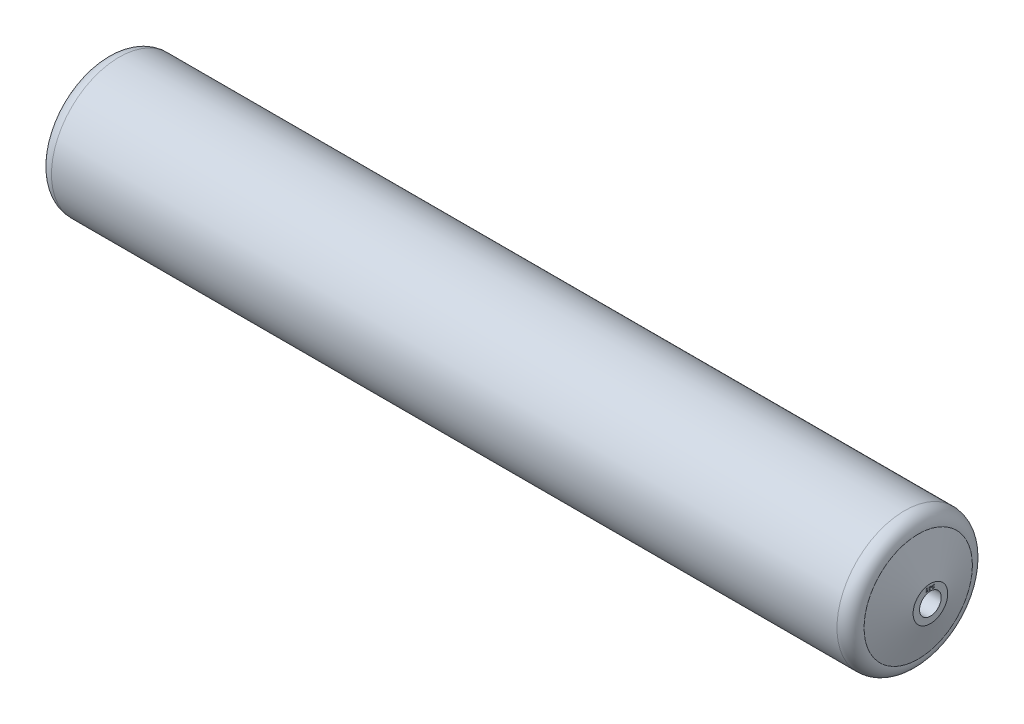
SolidWorks part; units mm, degrees
ref_plane "Plan de face" through (0, 0, 0) normal (0, 0, 1) x (1, 0, 0)
ref_plane "Plan de dessus" through (0, 0, 0) normal (0, 1, 0) x (1, 0, 0)
ref_plane "Plan de droite" through (0, 0, 0) normal (1, 0, 0) x (0, 0, -1)
sketch "Esquisse1" plane through (0, 0, 0) normal (0, 0, 1) x (1, 0, 0)
  line L0 (-154.5, 6.4) -> (-154.5, 0)
  line L1 (-154.5, 0) -> (154.5, 0)
  line L2 (154.5, 0) -> (154.5, 6.4)
  line L3 (154.5, 6.4) -> (150, 20)
  line L4 (145, 25) -> (-145, 25)
  line L5 (-150, 20) -> (-154.5, 6.4)
  line L6 (-154.5, 0) -> (154.5, 0) construction
  arc A0 (150, 20) -> (145, 25) centre (145, 20) ccw
  arc A1 (-145, 25) -> (-150, 20) centre (-145, 20) ccw
revolve "Révolution1" add sketch "Esquisse1" angle 360 about L6
sketch "Esquisse2" plane through (154.5, 0, 0) normal (1, 0, 0) x (0, 0, -1)
  line L0 (-0.221, 4.8437) -> (0.0166, 4.8437)
  line L1 (0.0166, 5.625) -> (-0.5335, 5.625)
  line L2 (-0.5335, 5.625) -> (-0.5335, 4.375)
  line L3 (-0.5335, 4.375) -> (-0.221, 4.375)
  line L4 (-0.221, 4.375) -> (-0.221, 4.8437)
  arc A0 (0.0166, 4.8437) -> (0.0166, 5.625) centre (0.0166, 5.2344) ccw
extrude "Enlèv. mat.-Extru.1" cut sketch "Esquisse2" against normal blind 0.1
sketch "Esquisse3" plane through (154.4, 0, 0) normal (1, 0, 0) x (0, 0, -1)
  line L0 (-0.221, 5.3906) -> (0.0166, 5.3906)
  line L1 (0.0166, 5.0781) -> (-0.221, 5.0781)
  line L2 (-0.221, 5.0781) -> (-0.221, 5.3906)
  arc A0 (0.0166, 5.3906) -> (0.0166, 5.0781) centre (0.0166, 5.2344) cw
extrude "Boss.-Extru.1" add sketch "Esquisse3" along normal blind 0.1
sketch "Esquisse4" plane through (154.5, 0, 0) normal (1, 0, 0) x (0, 0, -1)
  line L0 (-1.0016, 5.1563) -> (-1.3141, 5.1563)
  line L1 (-1.3141, 5.1563) -> (-1.3141, 5.625)
  line L2 (-1.3141, 5.625) -> (-1.6266, 5.625)
  line L3 (-1.6266, 5.625) -> (-1.6266, 4.375)
  line L4 (-1.6266, 4.375) -> (-1.3141, 4.375)
  line L5 (-1.3141, 4.375) -> (-1.3141, 4.8438)
  line L6 (-1.3141, 4.8438) -> (-1.0016, 4.8438)
  line L7 (-1.0016, 4.8438) -> (-1.0016, 4.375)
  line L8 (-1.0016, 4.375) -> (-0.6891, 4.375)
  line L9 (-0.6891, 4.375) -> (-0.6891, 5.625)
  line L10 (-0.6891, 5.625) -> (-1.0016, 5.625)
  line L11 (-1.0016, 5.625) -> (-1.0016, 5.1563)
extrude "Enlèv. mat.-Extru.2" cut sketch "Esquisse4" against normal blind 0.1
sketch "Esquisse5" plane through (154.5, 0, 0) normal (1, 0, 0) x (0, 0, -1)
  arc A0 (1.6266, 5.4419) -> (1.6266, 4.5581) centre (1.1846, 5) ccw
  arc A1 (1.4056, 4.779) -> (1.4056, 5.221) centre (1.1846, 5) cw
  spline S0 degree 3 poles (1.4056, 4.779) (1.4792, 4.7054) (1.5529, 4.6317) (1.6266, 4.5581) knots 0 0 0 0 1 1 1 1
  spline S1 degree 3 poles (1.6266, 5.4419) (1.5529, 5.3683) (1.4792, 5.2946) (1.4056, 5.221) knots 0 0 0 0 1 1 1 1
extrude "Enlèv. mat.-Extru.3" cut sketch "Esquisse5" against normal blind 0.1
hole_wizard "Diamètre du perçage Ø8.0 (8)1" positions "Esquisse7" profile "Esquisse6" hole size "Ø8.0" standard "Ansi Metric"
sketch "Esquisse7" plane through (-154.5, 0, 0) normal (-1, 0, 0) x (0, 0, 1)
  point P0 (0, 0)
sketch "Esquisse6" plane through (-154.5, 0, 0) normal (0, 1, 0) x (0, 0, 1)
  line L0 (0, 0) -> (0, 309)
  line L1 (0, 309) -> (4, 309)
  line L2 (4, 309) -> (4, 0)
  line L5 (4, 0) -> (0, 0)
  line L11 (0, -6.35) -> (0, 107.95) construction
  dimension "Diamètre du perçage jusqu'au prochain" = 8
  dimension "Profondeur du perçage jusqu'au prochain" = 309
